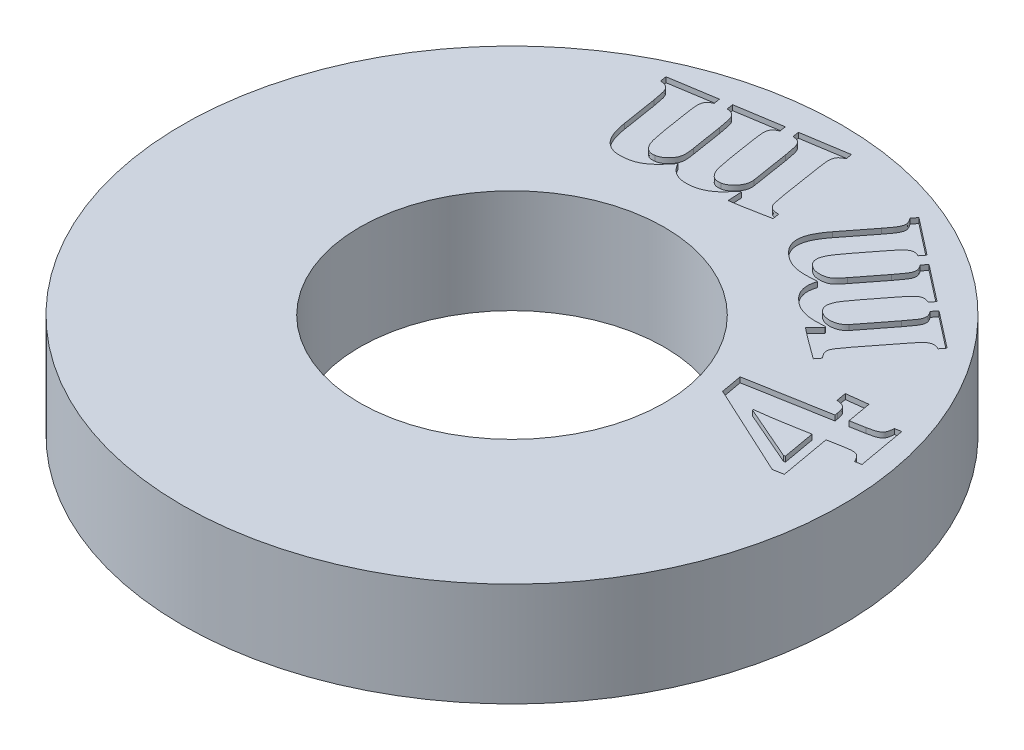
SolidWorks part; units mm, degrees
ref_plane "Front Plane" through (0, 0, 0) normal (0, 0, 1) x (1, 0, 0)
ref_plane "Top Plane" through (0, 0, 0) normal (0, 1, 0) x (1, 0, 0)
ref_plane "Right Plane" through (0, 0, 0) normal (1, 0, 0) x (0, 0, -1)
sketch "Sketch1" plane through (0, 0, 0) normal (0, 1, 0) x (1, 0, 0)
  circle A0 centre (0, 0) radius 12.7
  dimension "D1" = 25.4
extrude "Boss-Extrude1" add sketch "Sketch1" along normal blind 4
sketch "Sketch2" plane through (0, 0, 0) normal (0, -1, 0) x (-1, 0, 0)
  circle A0 centre (0, 0) radius 5.8674
  dimension "D1" = 11.7348
extrude "Cut-Extrude1" cut sketch "Sketch2" against normal through all
sketch "Sketch4" plane through (0, 4, 0) normal (0, 1, 0) x (1, 0, 0)
  circle A0 centre (0, 0) radius 12.0429 construction
  text T0 "<b>4mm</b>" font "Cambria" height 5.08
extrude "Cut-Extrude2" cut sketch "Sketch4" against normal blind 0.2
